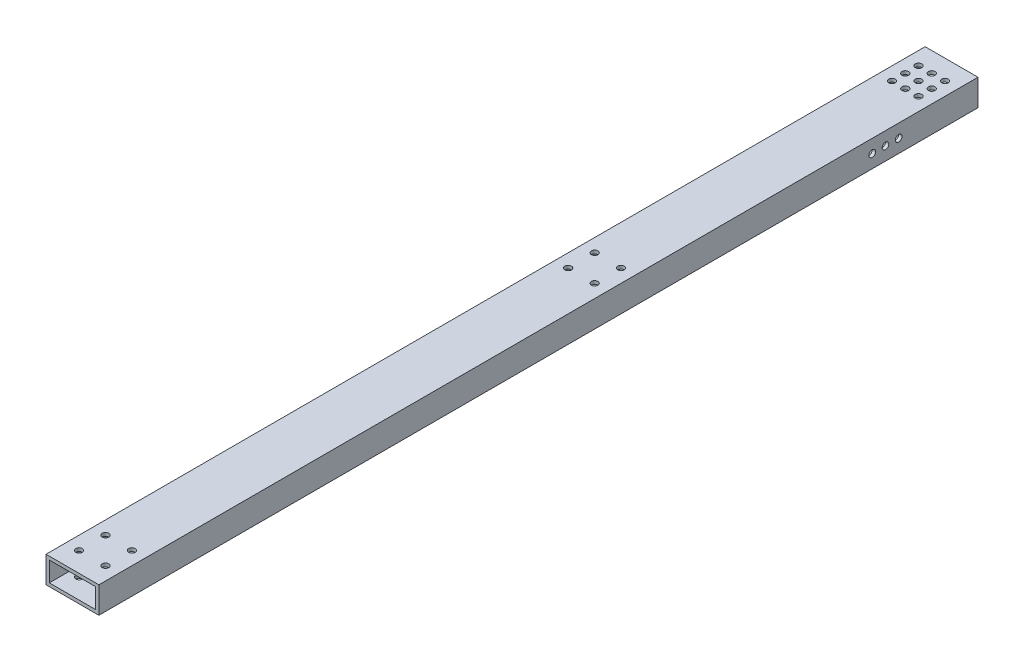
SolidWorks part; units mm, degrees
ref_plane "Front Plane" through (0, 0, 0) normal (0, 0, 1) x (1, 0, 0)
ref_plane "Top Plane" through (0, 0, 0) normal (0, 1, 0) x (1, 0, 0)
ref_plane "Right Plane" through (0, 0, 0) normal (1, 0, 0) x (0, 0, -1)
sketch "Sketch1" plane through (0, 0, 0) normal (0, 0, 1) x (1, 0, 0)
  line L0 (3.175, 22.225) -> (47.625, 22.225)
  line L1 (0, 0) -> (50.8, 0)
  line L2 (0, 0) -> (0, 25.4)
  line L3 (0, 25.4) -> (50.8, 25.4)
  line L4 (50.8, 0) -> (50.8, 25.4)
  line L5 (47.625, 3.175) -> (47.625, 22.225)
  line L6 (3.175, 3.175) -> (47.625, 3.175)
  line L7 (3.175, 3.175) -> (3.175, 22.225)
  dimension "D1" = 50.8
  dimension "D2" = 25.4
  dimension "D3" = 3.175
extrude "Boss-Extrude1" add sketch "Sketch1" along normal blind 844.55
sketch "Sketch2" plane through (50.8, 0, 0) normal (1, 0, 0) x (0, 0, -1)
  line L2 (0, 12.7) -> (-76.2, 12.7) construction
  line L3 (0, 0) -> (0, 25.4) construction
  circle A3 centre (-76.2, 12.7) radius 3.175
  circle A4 centre (-88.9, 12.7) radius 3.175
  circle A5 centre (-101.6, 12.7) radius 3.175
  dimension "D6" = 6.35
  dimension "D7" = 76.2
  dimension "D8" = 12.7
  dimension "D5" = 3
extrude "Cut-Extrude1" cut sketch "Sketch2" against normal through all both
sketch "Sketch3" plane through (0, 25.4, 0) normal (0, 1, 0) x (1, 0, 0)
  line L0 (12.7, 0) -> (12.7, -19.05) construction
  line L1 (50.8, 0) -> (0, 0) construction
  line L2 (12.7, -19.05) -> (0, -19.05) construction
  line L3 (0, -844.55) -> (0, 0) construction
  line L4 (12.7, -31.75) -> (12.7, -19.05) construction
  circle A0 centre (12.7, -19.05) radius 3.175
  circle A1 centre (25.4, -19.05) radius 3.175
  circle A2 centre (38.1, -19.05) radius 3.175
  circle A3 centre (25.4, -31.75) radius 3.175
  circle A4 centre (38.1, -31.75) radius 3.175
  circle A5 centre (25.4, -44.45) radius 3.175
  circle A6 centre (38.1, -44.45) radius 3.175
  circle A7 centre (12.7, -31.75) radius 3.175
  circle A8 centre (12.7, -44.45) radius 3.175
  dimension "D3" = 6.35
  dimension "D1" = 19.05
  dimension "D2" = 12.7
  dimension "D5" = 12.7
  dimension "D6" = 12.7
  dimension "D4" = 3
extrude "Cut-Extrude2" cut sketch "Sketch3" against normal through all both
sketch "Sketch4" plane through (0, 25.4, 0) normal (0, 1, 0) x (1, 0, 0)
  line L0 (25.4, 0) -> (25.4, -330.2) construction
  line L1 (50.8, 0) -> (0, 0) construction
  line L2 (0, -844.55) -> (0, 0) construction
  line L3 (12.7, -330.2) -> (0, -330.2) construction
  line L6 (0, -330.2) -> (0, -342.9) construction
  line L8 (50.8, -844.55) -> (50.8, 0) construction
  line L9 (12.7, -330.2) -> (38.1, -330.2) construction
  line L10 (12.7, -330.2) -> (12.7, -355.6) construction
  line L11 (12.7, -355.6) -> (38.1, -355.6) construction
  line L12 (38.1, -330.2) -> (38.1, -355.6) construction
  circle A0 centre (12.7, -330.2) radius 3.175
  circle A1 centre (38.1, -330.2) radius 3.175
  circle A2 centre (12.7, -355.6) radius 3.175
  circle A3 centre (38.1, -355.6) radius 3.175
  dimension "D2" = 6.35
  dimension "D5" = 6.35
  dimension "D6" = 6.35
  dimension "D7" = 6.35
  dimension "D1" = 330.2
  dimension "D3" = 25.4
  dimension "D4" = 25.4
  dimension "D8" = 12.7
  dimension "D9" = 330.2
extrude "Cut-Extrude3" cut sketch "Sketch4" against normal through all
sketch "Sketch5" plane through (0, 25.4, 0) normal (0, 1, 0) x (1, 0, 0)
  line L1 (0, -844.55) -> (12.7, -844.55) construction
  line L2 (0, -844.55) -> (0, -825.5) construction
  line L3 (0, -825.5) -> (12.7, -825.5) construction
  line L4 (12.7, -844.55) -> (12.7, -825.5) construction
  line L5 (12.7, -825.5) -> (38.1, -825.5) construction
  line L6 (12.7, -825.5) -> (12.7, -800.1) construction
  line L7 (12.7, -800.1) -> (38.1, -800.1) construction
  line L8 (38.1, -825.5) -> (38.1, -800.1) construction
  circle A0 centre (12.7, -825.5) radius 3.175
  circle A1 centre (38.1, -825.5) radius 3.175
  circle A2 centre (38.1, -800.1) radius 3.175
  circle A3 centre (12.7, -800.1) radius 3.175
  dimension "D3" = 6.35
  dimension "D6" = 6.35
  dimension "D7" = 6.35
  dimension "D8" = 6.35
  dimension "D1" = 19.05
  dimension "D2" = 12.7
  dimension "D4" = 25.4
  dimension "D5" = 25.4
extrude "Cut-Extrude4" cut sketch "Sketch5" against normal through all
